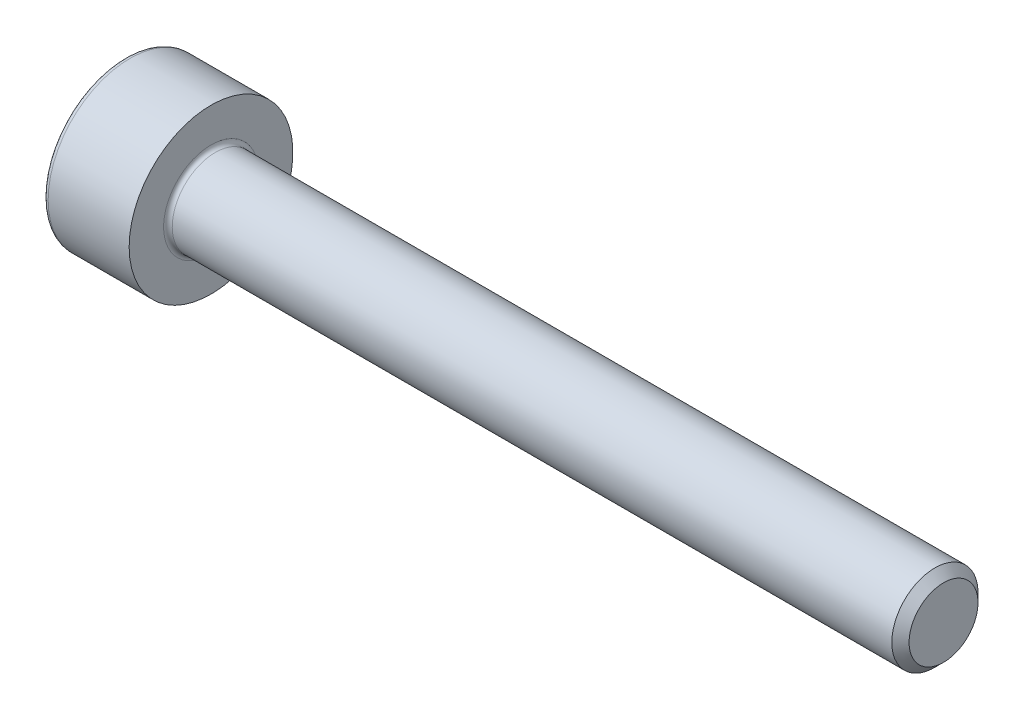
SolidWorks part; units mm, degrees
ref_plane "Front Plane" through (0, 0, 0) normal (0, 0, 1) x (1, 0, 0)
ref_plane "Top Plane" through (0, 0, 0) normal (0, 1, 0) x (1, 0, 0)
ref_plane "Right Plane" through (0, 0, 0) normal (1, 0, 0) x (0, 0, -1)
sketch "Sketch1" plane through (0, 0, 0) normal (0, 0, 1) x (1, 0, 0)
  line L0 (0, 0) -> (0, 1.9)
  line L1 (0, 1.9) -> (2, 1.9)
  line L2 (2, 1.9) -> (2, 0)
  line L3 (0, 0) -> (4.2799, 0) construction
  line L4 (2, 0) -> (19, 0)
  line L5 (19, 0) -> (19, 1)
  line L6 (19, 1) -> (2, 1)
  dimension "D1" = 17
revolve "Revolve1" add sketch "Sketch1" angle 360 about L3
fillet "Fillet1" radius 0.1 1 edges at (2, 0, 1)
fillet "Fillet2" radius 0.12 1 edges at (0, 0, 1.9)
chamfer "Chamfer1" distance 0.2 angle 45 1 edges at (19, 0, 1)
sketch "Sketch2" plane through (0, 0, 0) normal (-1, 0, 0) x (0, 0, 1)
  line L1 (0, 0.866) -> (-0.75, 0.433)
  line L2 (-0.75, 0.433) -> (-0.75, -0.433)
  line L3 (-0.75, -0.433) -> (0, -0.866)
  line L4 (0, -0.866) -> (0.75, -0.433)
  line L5 (0.75, -0.433) -> (0.75, 0.433)
  line L6 (0.75, 0.433) -> (0, 0.866)
  circle A0 centre (0, 0) radius 0.75 construction
extrude "Extrude1" cut sketch "Sketch2" against normal blind 1
